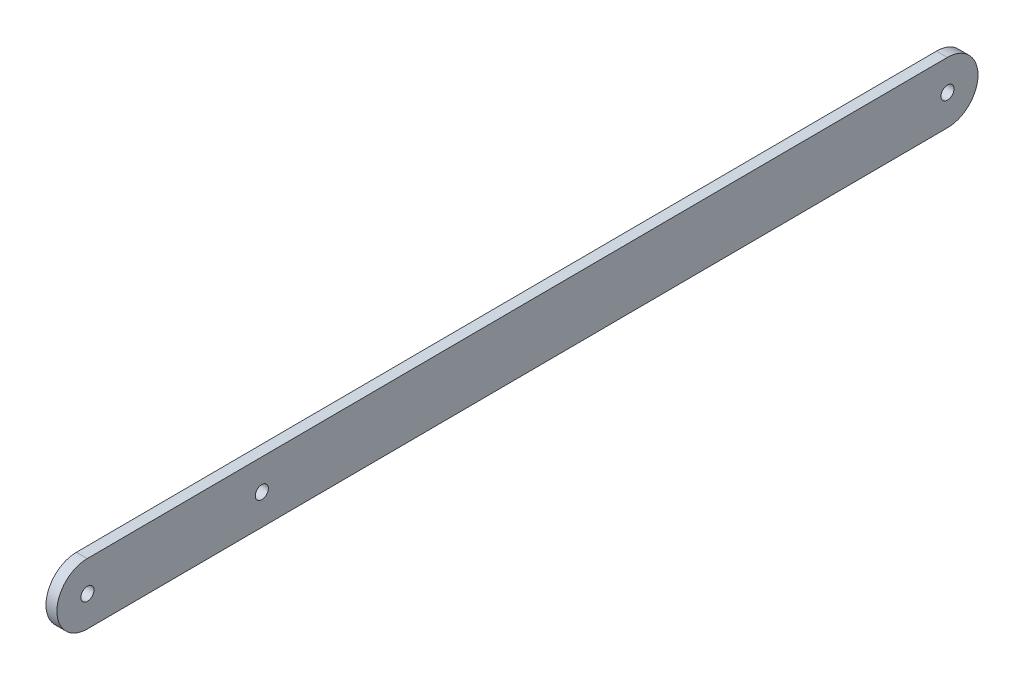
SolidWorks part; units mm, degrees
material "Acrylic (Medium-high impact)"
ref_plane "Ground" through (0, 0, 0) normal (0, 0, 1) x (1, 0, 0)
ref_plane "Right" through (0, 0, 0) normal (0, 1, 0) x (1, 0, 0)
ref_plane "Front" through (0, 0, 0) normal (1, 0, 0) x (0, 0, -1)
sketch "Sketch1" plane through (0, 0, 0) normal (1, 0, 0) x (0, 0, -1)
  line L0 (0, 0.913) -> (-197.28, 0) construction
  line L1 (0.0324, -6.0869) -> (-197.2476, -6.9999)
  line L2 (-0.0324, 7.9129) -> (-197.3124, 6.9999)
  arc A0 (0.0324, -6.0869) -> (-0.0324, 7.9129) centre (0, 0.913) ccw
  arc A1 (-197.3124, 6.9999) -> (-197.2476, -6.9999) centre (-197.28, 0) ccw
  circle A2 centre (-197.28, 0) radius 1.5
  circle A3 centre (0, 0.913) radius 1.5
  circle A4 centre (-157.28, 0.1851) radius 1.5
  point P2 (-98.64, 0.4565)
  dimension "D2" = 7
  dimension "D3" = 3
  dimension "D1" = 197.28
  dimension "D4" = 40
extrude "Boss-Extrude1" add sketch "Sketch1" along normal blind 2.5
